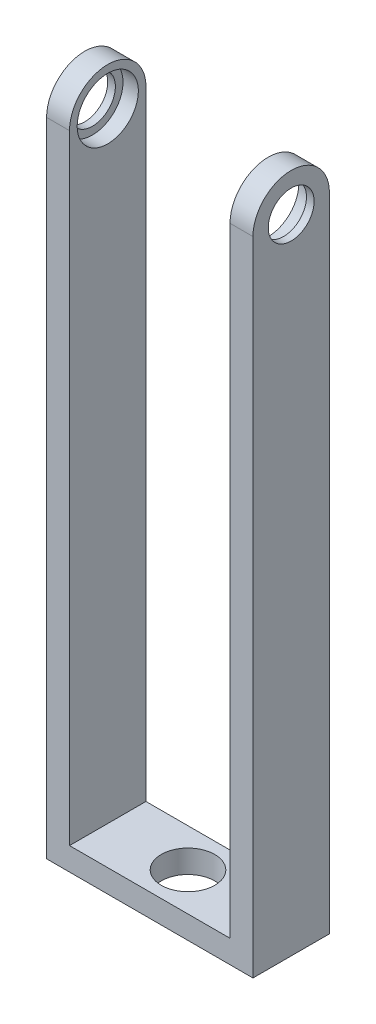
SolidWorks part; units mm, degrees
ref_plane "Front Plane" through (0, 0, 0) normal (0, 0, 1) x (1, 0, 0)
ref_plane "Top Plane" through (0, 0, 0) normal (0, 1, 0) x (1, 0, 0)
ref_plane "Right Plane" through (0, 0, 0) normal (1, 0, 0) x (0, 0, -1)
sketch "Sketch1" plane through (0, 0, 0) normal (0, 1, 0) x (1, 0, 0)
  line L1 (-13.5, -5) -> (13.5, -5)
  line L2 (-13.5, -5) -> (-13.5, 5)
  line L3 (-13.5, 5) -> (13.5, 5)
  line L4 (13.5, -5) -> (13.5, 5)
  line L5 (0, 5) -> (0, -5) construction
  line L6 (-13.5, 0) -> (13.5, 0) construction
  point P1 (0, 0)
  dimension "D1" = 10
  dimension "D2" = 27
extrude "Boss-Extrude1" add sketch "Sketch1" along normal blind 3
sketch "Sketch3" plane through (0, 0, 0) normal (1, 0, 0) x (0, 0, -1)
  line L0 (0, 0) -> (0, 16.3575) construction
sketch3d "3DSketch1" plane through (0, 0, 0) normal (0, 0, 1) x (1, 0, 0)
  dimension "D1" = 13.5
sketch "Sketch5" plane through (13.5, 0, 0) normal (1, 0, 0) x (0, 0, -1)
  line L0 (5.5, 0) -> (-5.5, 0) construction
  line L1 (-5, 3) -> (5, 3)
  line L2 (-5, 3) -> (-5, 84)
  line L4 (5, 3) -> (5, 84)
  arc A0 (-5, 84) -> (5, 84) centre (0, 84) cw
  circle A1 centre (0, 84) radius 3
  dimension "D2" = 6
  dimension "D1" = 84
extrude "Boss-Extrude3" add sketch "Sketch5" against normal blind 3
sketch "Sketch6" plane through (0, 3, 0) normal (0, 1, 0) x (1, 0, 0)
  circle A0 centre (0, 0) radius 1.5
  dimension "D1" = 3
extrude "Cut-Extrude1" cut sketch "Sketch6" against normal blind 3
sketch "Sketch7" plane through (10.5, 0, 0) normal (-1, 0, 0) x (0, 0, 1)
  circle A0 centre (0, 84) radius 4
  dimension "D1" = 8
extrude "Cut-Extrude2" cut sketch "Sketch7" against normal blind 2
mirror "Mirror3" about plane through (0, 0, 0) normal (1, 0, 0) of "Cut-Extrude2", "Boss-Extrude3", "Boss-Extrude1"
sketch "Sketch8" plane through (0, 3, 0) normal (0, 1, 0) x (1, 0, 0)
  circle A0 centre (0, 0) radius 3.5
  dimension "D1" = 7
extrude "Cut-Extrude4" cut sketch "Sketch8" against normal through all
